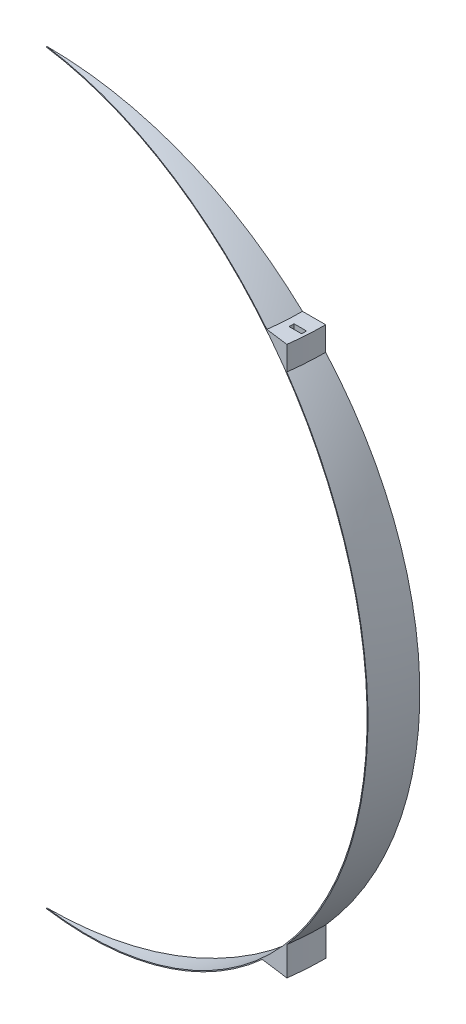
SolidWorks part; units mm, degrees
ref_plane "Front Plane" through (0, 0, 0) normal (0, 0, 1) x (1, 0, 0)
ref_plane "Top Plane" through (0, 0, 0) normal (0, 1, 0) x (1, 0, 0)
ref_plane "Right Plane" through (0, 0, 0) normal (1, 0, 0) x (0, 0, -1)
sketch "Sketch2" plane through (0, 0, 0) normal (0, 0, 1) x (1, 0, 0)
  line L0 (0, 993.0752) -> (0, 990.6)
  line L1 (0, -990.6) -> (0, -993.0752)
  line L4 (742.757, 659.1741) -> (742.757, 722.7151)
  line L5 (742.757, 722.7151) -> (681.0884, 722.7151)
  line L7 (742.9731, -658.9305) -> (742.9731, -735.9651)
  line L8 (742.9731, -735.9651) -> (666.7487, -735.9651)
  arc A0 (0, 990.6) -> (0, -990.6) centre (0, 0) cw
  arc A1 (0, -993.0752) -> (666.7487, -735.9651) centre (0, 0) ccw
  arc A2 (681.0884, 722.7151) -> (0, 993.0752) centre (0, 0) ccw
  arc A3 (742.9731, -658.9305) -> (742.757, 659.1741) centre (0, 0) ccw
  dimension "D1" = 990.6
revolve "Revolve2" add sketch "Sketch2" angle 7.5 about L0
sketch "Sketch4" plane through (0, -735.9651, 0) normal (0, -1, 0) x (1, 0, 0)
  line L1 (688.6335, 42.5614) -> (721.8835, 42.5614)
  line L2 (688.6335, 42.5614) -> (688.6335, 55.5614)
  line L3 (688.6335, 55.5614) -> (721.8835, 55.5614)
  line L4 (721.8835, 42.5614) -> (721.8835, 55.5614)
sketch "Sketch7" plane through (0, 722.7151, 0) normal (0, 1, 0) x (-1, 0, 0)
  line L1 (-731.6247, 39.9227) -> (-698.3747, 39.9227)
  line L2 (-731.6247, 39.9227) -> (-731.6247, 52.9227)
  line L3 (-731.6247, 52.9227) -> (-698.3747, 52.9227)
  line L4 (-698.3747, 39.9227) -> (-698.3747, 52.9227)
extrude "Cut-Extrude5" cut sketch "Sketch4" against normal blind 19
extrude "Cut-Extrude7" cut sketch "Sketch7" against normal blind 19
